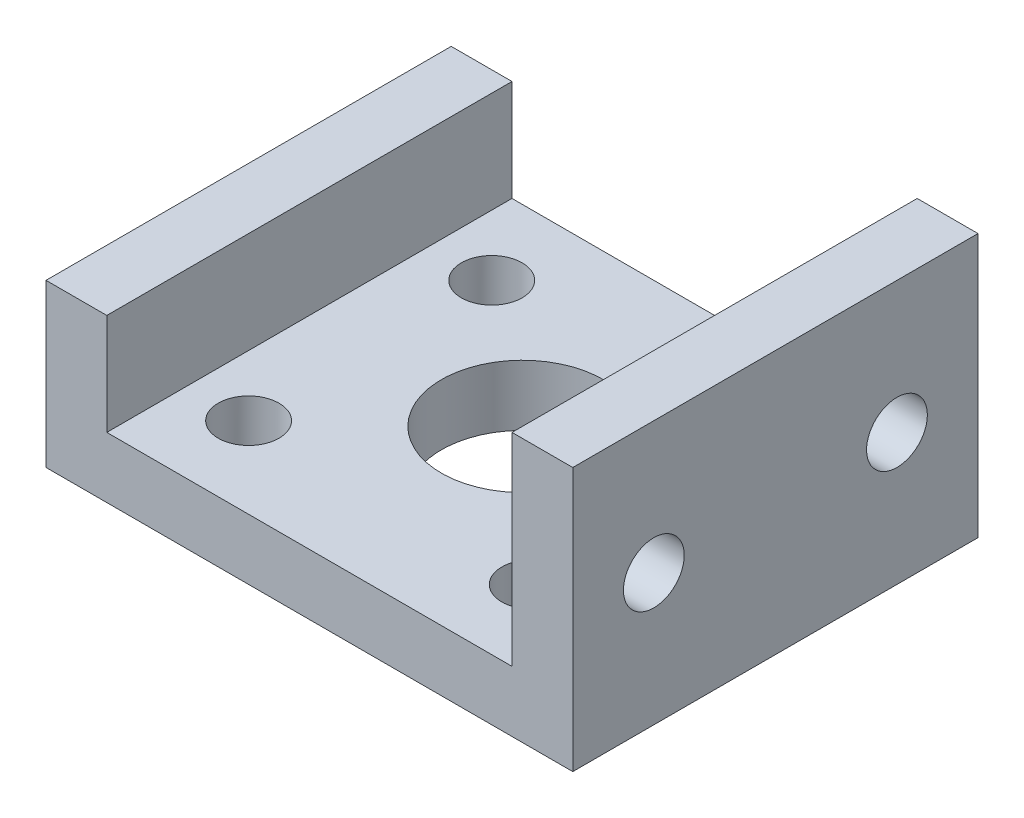
SolidWorks part; units mm, degrees
ref_plane "前视基准面" through (0, 0, 0) normal (0, 0, 1) x (1, 0, 0)
ref_plane "上视基准面" through (0, 0, 0) normal (0, 1, 0) x (1, 0, 0)
ref_plane "右视基准面" through (0, 0, 0) normal (1, 0, 0) x (0, 0, -1)
other "Configuration Table"
sketch "草图1" plane through (0, 0, 0) normal (0, 0, 1) x (1, 0, 0)
  line L9 (-8.64, -35.5) -> (-8.64, -39.5)
  line L10 (17.36, 39.5) -> (-8.64, 39.5)
  line L15 (55, 0) -> (-55, 0) construction
  line L22 (17.36, 39.5) -> (17.36, -39.5)
  line L23 (17.36, -39.5) -> (-8.64, -39.5)
  line L24 (-8.64, 39.5) -> (-8.64, 35.5)
  line L25 (14.36, 36.5) -> (-5.64, 36.5)
  line L26 (14.36, 36.5) -> (14.36, -36.5)
  line L27 (14.36, -36.5) -> (-5.64, -36.5)
  line L28 (-8.64, 35.5) -> (-8.64, 31.5)
  line L29 (-8.64, 31.5) -> (-5.64, 31.5)
  line L30 (-5.64, 36.5) -> (-5.64, 31.5)
  line L31 (-8.64, -31.5) -> (-5.64, -31.5)
  line L32 (-5.64, -36.5) -> (-5.64, -31.5)
  line L34 (-8.64, -35.5) -> (-8.64, -31.5)
  point P0 (0, 0)
  point P7 (0, 0)
  dimension "D1" = 79
  dimension "D2" = 3
  dimension "D3" = 3
  dimension "D4" = 3
  dimension "D5" = 26
  dimension "D6" = 63
  dimension "D7" = 3
extrude "凸台-拉伸1" add sketch "草图1" along normal blind 160
sketch "草图4" plane through (14.36, 0, 0) normal (-1, 0, 0) x (0, 0, 1)
  line L0 (160, -31.5) -> (0, -31.5) construction
  line L1 (140, 26.5) -> (160, 26.5)
  line L3 (140, -26.5) -> (160, -26.5)
  line L4 (160, 26.5) -> (160, -26.5)
  line L5 (140, 26.5) -> (160, -26.5) construction
  line L6 (140, -26.5) -> (160, 26.5) construction
  line L7 (160, 36.5) -> (160, -36.5) construction
  line L12 (140, 26.5) -> (140, 45.304)
  line L13 (100, -45.304) -> (110, -45.304)
  line L14 (110, -45.304) -> (110, -26.5)
  line L15 (110, -26.5) -> (130, -26.5)
  line L16 (130, -45.304) -> (140, -45.304)
  line L17 (140, -45.304) -> (140, -26.5)
  line L18 (140, 45.304) -> (130, 45.304)
  line L19 (130, 45.304) -> (130, 26.5)
  line L21 (110, 26.5) -> (130, 26.5)
  line L22 (110, 26.5) -> (110, 45.304)
  line L23 (110, 45.304) -> (100, 45.304)
  line L30 (100, 45.304) -> (100, 26.5)
  line L31 (72.3419, -45.304) -> (80, -45.304)
  line L34 (80, -45.304) -> (80, -26.5)
  line L35 (80, -26.5) -> (100, -26.5)
  line L39 (80, 26.5) -> (100, 26.5)
  line L42 (80, 26.5) -> (80, 45.304)
  line L43 (80, 45.304) -> (72.3419, 45.304)
  line L45 (100, -26.5) -> (100, -45.304)
  line L46 (130, -26.5) -> (130, -45.304)
  line L47 (72.3419, 45.304) -> (72.3419, 47.203)
  line L48 (-21.5766, -47.2023) -> (72.3419, -47.2023)
  line L49 (72.3419, -47.2023) -> (72.3419, -45.304)
  line L50 (72.3419, 47.203) -> (-21.5766, 47.203)
  line L51 (-21.5766, 47.203) -> (-21.5766, -47.2023)
  line L66 (100, 26.5) -> (100, -26.5) [skipped]
  line L67 (130, 26.5) -> (130, -26.5) [skipped]
  line L68 (70, 45.304) -> (70, -45.304) [skipped]
  point P10 (150, 0)
  dimension "D1" = 53
  dimension "D2" = 5
  dimension "D3" = 10
  dimension "D4" = 20
extrude "切除-拉伸2" cut sketch "草图4" against normal through all and the other way through all
sketch "草图5" plane through (17.36, 0, 0) normal (1, 0, 0) x (0, 0, -1)
  line L0 (-80, -26.5) -> (-100, -26.5) construction
  line L1 (-100, -26.5) -> (-100, -39.5) construction
  line L2 (-80, -39.5) -> (-80, -26.5) construction
  line L3 (-103.1277, -33) -> (-76.998, -33) construction
  line L4 (-100, -39.5) -> (-80, -39.5) construction
  line L5 (14.3, 0) -> (-14.3, 0) construction
  circle A0 centre (-96, -33) radius 1.5
  circle A1 centre (-84, -33) radius 1.5
  circle A24 centre (-126, -33) radius 1.5
  circle A26 centre (-114, -33) radius 1.5
  circle A28 centre (-156, -33) radius 1.5
  circle A30 centre (-144, -33) radius 1.5
  circle A34 centre (-84, 33) radius 1.5
  circle A35 centre (-96, 33) radius 1.5
  circle A37 centre (-114, 33) radius 1.5
  circle A39 centre (-126, 33) radius 1.5
  circle A41 centre (-144, 33) radius 1.5
  circle A43 centre (-156, 33) radius 1.5
  dimension "D1" = 6.5
  dimension "D3" = 4
  dimension "D2" = 4
  dimension "D4" = 3
  dimension "D6" = 6.5
  dimension "D7" = 6.5
extrude "切除-拉伸3" cut sketch "草图5" against normal up to next (3 mm away)
sketch "草图6" plane through (0, -39.5, 0) normal (0, -1, 0) x (1, 0, 0)
  line L0 (17.36, 100) -> (-8.64, 100) construction
  line L1 (-8.64, 80) -> (17.36, 80) construction
  line L2 (17.36, 100) -> (17.36, 80) construction
  line L3 (4.36, 100) -> (4.36, 78.9718) construction
  circle A0 centre (11.36, 96) radius 1.5
  circle A1 centre (11.36, 84) radius 1.5
  circle A2 centre (-2.64, 84) radius 1.5
  circle A3 centre (-2.64, 96) radius 1.5
  circle A4 centre (-2.64, 126) radius 1.5
  circle A5 centre (-2.64, 114) radius 1.5
  circle A6 centre (11.36, 114) radius 1.5
  circle A7 centre (11.36, 126) radius 1.5
  circle A8 centre (-2.64, 156) radius 1.5
  circle A9 centre (-2.64, 144) radius 1.5
  circle A10 centre (11.36, 144) radius 1.5
  circle A11 centre (11.36, 156) radius 1.5
  circle A12 centre (4.36, 89.4859) radius 4
  circle A13 centre (4.36, 119.4859) radius 4
  circle A14 centre (4.36, 149.4859) radius 4
  dimension "D1" = 4
  dimension "D6" = 3
  dimension "D2" = 4
  dimension "D3" = 6
  dimension "D4" = 6
  dimension "D5" = 3
extrude "切除-拉伸4" cut sketch "草图6" against normal up to next (3 mm away)
mirror "镜向1" about plane through (0, 0, 0) normal (0, 1, 0) of "切除-拉伸4"
delete or keep bodies "实体-删除/保留 1" type delete bodies bodies 136 134 138 137 139
equation "\"7。5\"=6.5"
